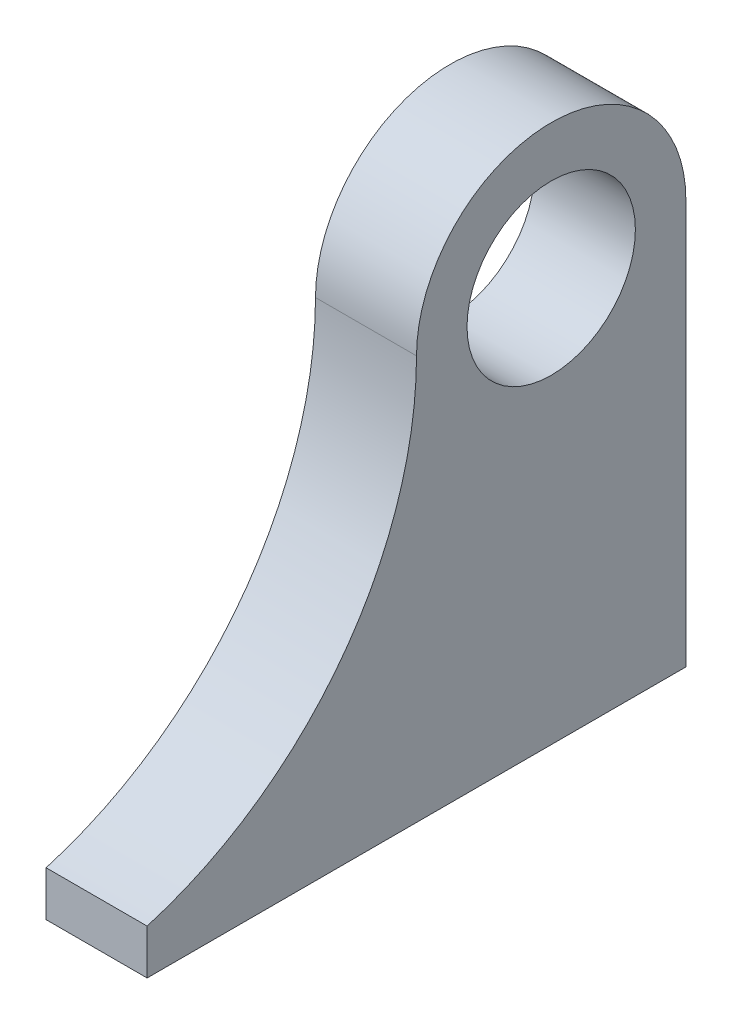
SolidWorks part; units mm, degrees
ref_plane "Alzado" through (0, 0, 0) normal (0, 0, 1) x (1, 0, 0)
ref_plane "Planta" through (0, 0, 0) normal (0, 1, 0) x (1, 0, 0)
ref_plane "Vista lateral" through (0, 0, 0) normal (1, 0, 0) x (0, 0, -1)
sketch "Croquis1" plane through (0, 0, 0) normal (0, 1, 0) x (1, 0, 0)
  line L0 (63.5, 63.5) -> (63.5, 390.652) construction
  line L1 (0, 0) -> (654.05, 0) construction
  line L2 (0, 0) -> (0, 454.152) construction
  line L3 (0, 454.152) -> (654.05, 454.152) construction
  line L4 (654.05, 0) -> (654.05, 454.152) construction
  line L5 (63.5, 390.652) -> (590.55, 390.652) construction
  line L6 (590.55, 63.5) -> (590.55, 390.652) construction
  line L7 (63.5, 63.5) -> (590.55, 63.5) construction
  line L8 (42.3333, 411.8187) -> (611.7167, 411.8187) construction
  line L9 (611.7167, 42.3333) -> (611.7167, 411.8187) construction
  line L10 (42.3333, 42.3333) -> (611.7167, 42.3333) construction
  line L11 (42.3333, 42.3333) -> (42.3333, 411.8187) construction
  line L12 (606.9542, 411.8187) -> (606.9542, 454.152) construction
  line L14 (606.9542, 454.152) -> (602.1917, 454.152)
  line L15 (606.9542, 454.152) -> (606.9542, 411.8187)
  line L16 (606.9542, 411.8187) -> (602.1917, 411.8187)
  line L17 (602.1917, 454.152) -> (602.1917, 411.8187)
  dimension "D1" = 654.05
  dimension "D2" = 454.152
  dimension "D3" = 42.3333
  dimension "D4" = 369.4853
  dimension "D5" = 63.5
  dimension "D6" = 569.3833
  dimension "D7" = 527.05
  dimension "D8" = 327.152
  dimension "D9" = 42.3333
  dimension "D10" = 4.7625
  dimension "D11" = 4.7625
  dimension "D12" = 42.3333
  dimension "D13" = 21.1667
extrude "Saliente-Extruir1" add sketch "Croquis1" along normal blind 25.4
sketch "Croquis2" plane through (606.9542, 0, 0) normal (1, 0, 0) x (0, 0, -1)
  line L0 (432.9853, 25.4) -> (432.9853, 0) construction
  line L1 (411.8187, 25.4) -> (454.152, 25.4) construction
  line L2 (411.8187, 0) -> (454.152, 0) construction
  line L3 (439.3353, 19.05) -> (439.3353, 0)
  line L4 (439.3353, 0) -> (413.9353, 0)
  line L5 (413.9353, 0) -> (411.8187, 0)
  line L6 (413.9353, 0) -> (411.8187, 0) construction
  line L7 (413.9353, 0) -> (413.9353, 2.12)
  line L8 (426.6353, 19.05) -> (432.9853, 19.05) construction
  line L9 (411.8187, 0) -> (411.8187, 25.4)
  line L10 (411.8187, 25.4) -> (454.152, 25.4)
  line L11 (454.152, 25.4) -> (454.152, 0)
  line L12 (454.152, 0) -> (439.3353, 0)
  circle A0 centre (432.9853, 19.05) radius 3.9688
  arc A1 (439.3353, 19.05) -> (426.6353, 19.05) centre (432.9853, 19.05) ccw
  arc A2 (413.9353, 2.12) -> (426.6353, 19.05) centre (409.0009, 19.05) ccw
  point P10 (432.9853, 19.05)
  line M4 (411.8187, 0) -> (454.152, 0)
  line M5 (454.152, 0) -> (454.152, 25.4)
  line M6 (454.152, 25.4) -> (411.8187, 25.4)
  line M7 (411.8187, 25.4) -> (411.8187, 0)
  dimension "D4" = 7.9375
  dimension "D5" = 2.12
  dimension "D3" = 6.35
  dimension "D1" = 25.4
  dimension "D2" = 2.1167
extrude "Cortar-Extruir1" cut sketch "Croquis2" against normal blind 25.4 contours L7 A2 A1 L10 M7 M4 | A1 L3 M4 M5 M6 | A0
